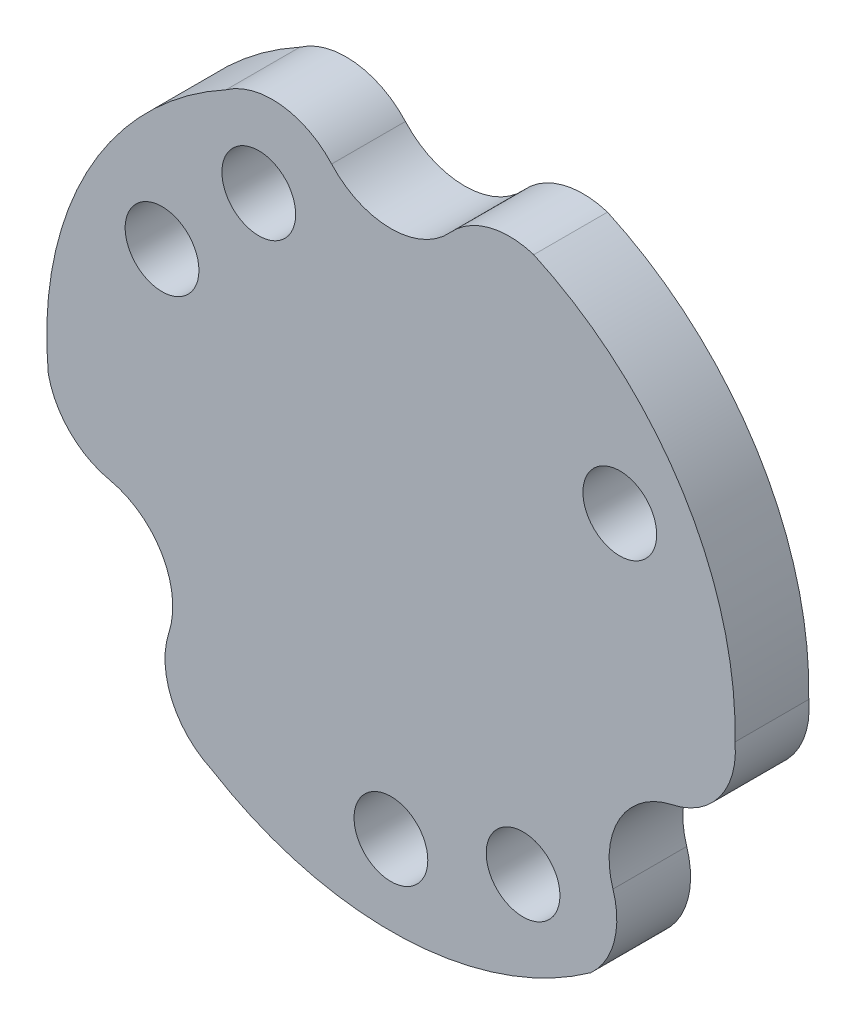
SolidWorks part; units mm, degrees
ref_plane "Plan de face" through (0, 0, 0) normal (0, 0, 1) x (1, 0, 0)
ref_plane "Plan de dessus" through (0, 0, 0) normal (0, 1, 0) x (1, 0, 0)
ref_plane "Plan de droite" through (0, 0, 0) normal (1, 0, 0) x (0, 0, -1)
sketch "Esquisse1" plane through (0, 0, 0) normal (0, 0, 1) x (1, 0, 0)
  line L0 (9.3098, 5.375) -> (0, -10.75) construction
  line L1 (0, -10.75) -> (-9.3098, 5.375) construction
  line L2 (-9.3098, 5.375) -> (9.3098, 5.375) construction
  line L3 (0, -10.75) -> (17.7301, -0.5135) construction
  line L5 (-9.3098, 5.375) -> (9.4568, 16.2099) construction
  arc A12 (-2.411, 11.8207) -> (2.411, 11.8207) centre (0, 14) ccw
  arc A16 (5.8094, 12.7378) -> (2.411, 11.8207) centre (4.8221, 9.6414) ccw
  arc A17 (-2.411, 11.8207) -> (-6.7074, 12.2887) centre (-4.8221, 9.6414) ccw
  arc A18 (-6.7074, 12.2887) -> (-13.9359, -1.3378) centre (0, 0) ccw
  arc A19 (8.1265, -11.4) -> (9.0315, -7.9984) centre (5.9386, -8.9967) ccw
  arc A20 (11.4425, -3.8223) -> (9.0315, -7.9984) centre (12.1244, -7) ccw
  arc A21 (11.4425, -3.8223) -> (13.996, -0.3356) centre (10.7607, -0.6447) ccw
  arc A23 (-13.9359, -1.3378) -> (-11.4425, -3.8223) centre (-10.7607, -0.6447) ccw
  arc A24 (-9.0315, -7.9984) -> (-11.4425, -3.8223) centre (-12.1244, -7) ccw
  arc A25 (-9.0315, -7.9984) -> (-7.2886, -11.9531) centre (-5.9386, -8.9967) ccw
  arc A27 (-7.2886, -11.9531) -> (8.1265, -11.4) centre (0, 0) ccw
  arc A28 (13.996, -0.3356) -> (5.8094, 12.7378) centre (0, 0) ccw
  circle A30 centre (0, 0) radius 10.75 construction
  circle A31 centre (9.3098, 5.375) radius 1.5
  circle A32 centre (0, -10.75) radius 1.5
  circle A33 centre (-9.3098, 5.375) radius 1.5
  circle A34 centre (9.3098, 5.375) radius 3.25 construction
  circle A35 centre (-9.3098, 5.375) radius 3.25 construction
  circle A36 centre (0, -10.75) radius 3.25 construction
  circle A37 centre (5.375, -9.3098) radius 1.5
  circle A39 centre (-5.375, 9.3098) radius 1.5
  circle A40 centre (-9.3098, -5.375) radius 1.5 [skipped]
  point P31 (0, 0)
  point P45 (0, 0)
  dimension "D2" = 3
  dimension "D3" = 6.5
  dimension "D4" = 6.5
  dimension "D5" = 90
  dimension "D8" = 14
  dimension "D9" = 3.25
  dimension "D10" = 6.5
  dimension "D11" = 3.25
  dimension "D12" = 90
  dimension "D13" = 4
  dimension "D6" = 60
  dimension "D7" = 60
  dimension "D14" = 10.78
  dimension "D15" = 10.78
extrude "Boss.-Extru.2" add sketch "Esquisse1" along normal blind 3
